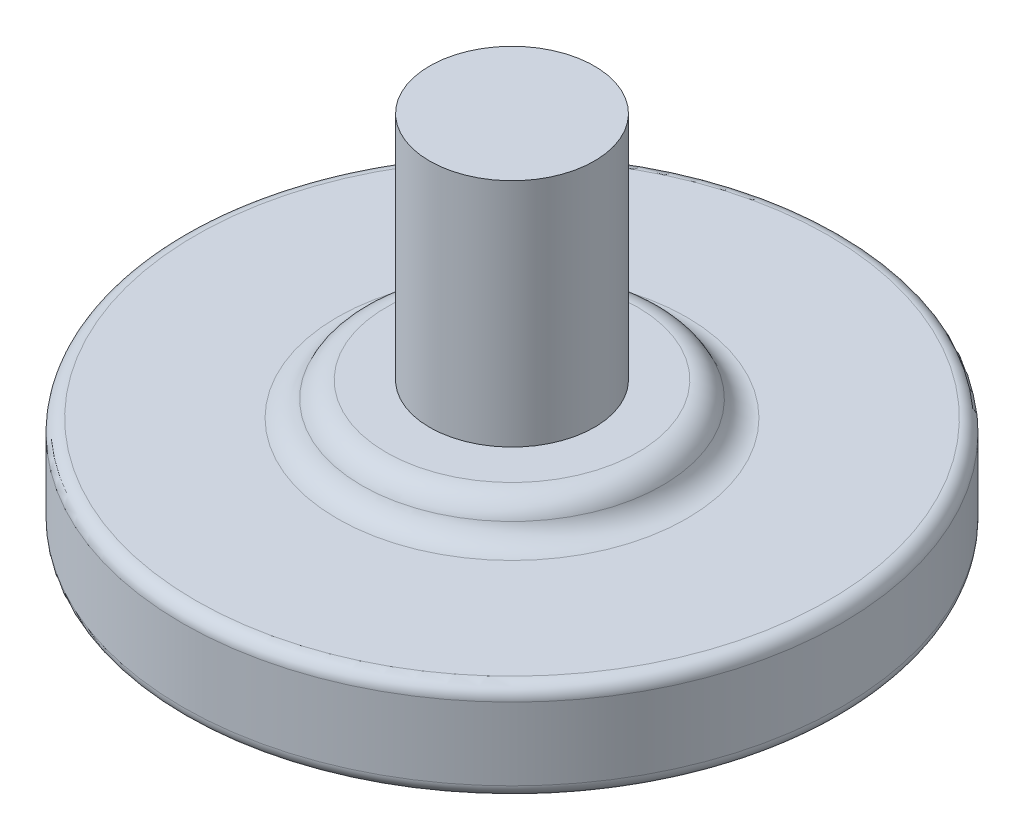
SolidWorks part; units mm, degrees
ref_plane "Front Plane" through (0, 0, 0) normal (0, 0, 1) x (1, 0, 0)
ref_plane "Top Plane" through (0, 0, 0) normal (0, 1, 0) x (1, 0, 0)
ref_plane "Right Plane" through (0, 0, 0) normal (1, 0, 0) x (0, 0, -1)
sketch "Sketch1" plane through (0, 0, 0) normal (0, 1, 0) x (1, 0, 0)
  circle A0 centre (0, 0) radius 10
  dimension "D1" = 20
extrude "Boss-Extrude1" add sketch "Sketch1" along normal blind 3
sketch "Sketch2" plane through (0, 3, 0) normal (0, 1, 0) x (1, 0, 0)
  circle A0 centre (0, 0) radius 2.5
  dimension "D1" = 5
extrude "Boss-Extrude2" add sketch "Sketch2" along normal blind 8
fillet "Fillet2" radius 0.4 2 edges at (0, 0, 10) (0, 3, 10)
sketch "Sketch3" plane through (0, 3, 0) normal (0, 1, 0) x (1, 0, 0)
  circle A0 centre (0, 0) radius 2.5
  circle A1 centre (0, 0) radius 4.5
  dimension "D1" = 9
extrude "Boss-Extrude3" add sketch "Sketch3" along normal blind 1
fillet "Fillet3" radius 0.8 1 edges at (0, 3, 4.5)
fillet "Fillet4" radius 0.8 1 edges at (0, 4, 4.5)
equation "\"D1@Boss-Extrude2\"=5+3"
